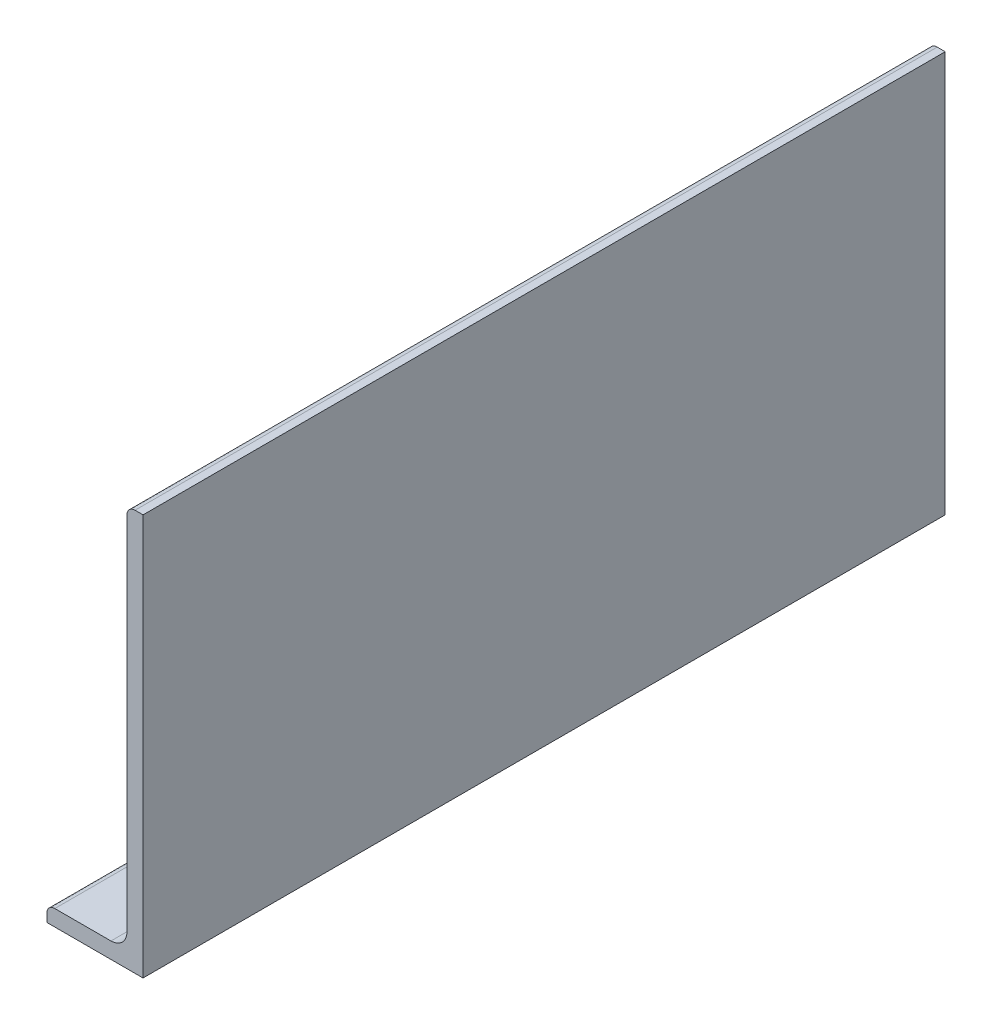
SolidWorks part; units mm, degrees
ref_plane "Front Plane" through (0, 0, 0) normal (0, 0, 1) x (1, 0, 0)
ref_plane "Top Plane" through (0, 0, 0) normal (0, 1, 0) x (1, 0, 0)
ref_plane "Right Plane" through (0, 0, 0) normal (1, 0, 0) x (0, 0, -1)
sketch "Sketch2" plane through (0, 0, 0) normal (0, 0, 1) x (1, 0, 0)
  line L0 (182.7535, 24.8288) -> (182.7535, -25.1712)
  line L1 (182.7535, -25.1712) -> (170.7535, -25.1712)
  line L2 (170.7535, -25.1712) -> (170.7535, -23.1712)
  line L3 (170.7535, -23.1712) -> (180.7535, -23.1712)
  line L4 (180.7535, -23.1712) -> (180.7535, 24.8288)
  line L5 (180.7535, 24.8288) -> (182.7535, 24.8288)
  dimension "D1" = 2
  dimension "D2" = 2
  dimension "D3" = 50
  dimension "D4" = 12
extrude "Boss-Extrude1" add sketch "Sketch2" along normal blind 100
fillet "Fillet2" radius 1 2 edges at (180.7535, 24.8288, 50) (170.7535, -23.1712, 50)
fillet "Fillet3" radius 2 1 edges at (180.7535, -23.1712, 50)
sketch "Sketch3" plane through (0, -23.1712, 0) normal (0, 1, 0) x (1, 0, 0)
  line L0 (178.7535, 0) -> (171.7535, 0) construction
  line L1 (178.7535, -100) -> (171.7535, -100) construction
  line L2 (170.7535, -100) -> (170.7535, 0) construction
  circle A0 centre (175.2535, -80) radius 1.6
  circle A1 centre (175.2535, -20) radius 1.6
  dimension "D1" = 20
  dimension "D2" = 20
  dimension "D3" = 4.5
  dimension "D4" = 4.5
  dimension "D5" = 3.2
  dimension "D6" = 3.2
extrude "Cut-Extrude1" cut sketch "Sketch3" against normal through all
